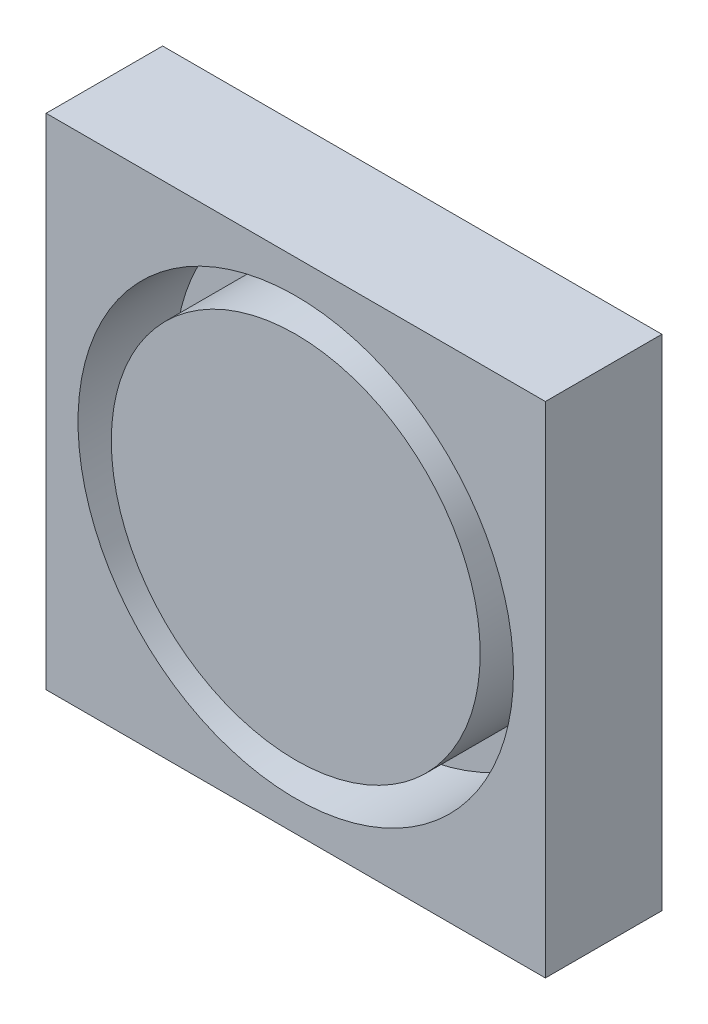
SolidWorks part; units mm, degrees
ref_plane "前视基准面" through (0, 0, 0) normal (0, 0, 1) x (1, 0, 0)
ref_plane "上视基准面" through (0, 0, 0) normal (0, 1, 0) x (1, 0, 0)
ref_plane "右视基准面" through (0, 0, 0) normal (1, 0, 0) x (0, 0, -1)
sketch "草图1" plane through (0, 0, 0) normal (0, 0, 1) x (1, 0, 0)
  line L1 (0, 0) -> (30, 0)
  line L2 (0, 0) -> (0, -30)
  line L3 (0, -30) -> (30, -30)
  line L4 (30, 0) -> (30, -30)
  dimension "D1" = 30
  dimension "D2" = 30
extrude "凸台-拉伸1" add sketch "草图1" along normal blind 7
ref_plane "基准面1" through (15, 0, 0) normal (-1, 0, 0) x (0, 0, 1)
sketch "草图5" plane through (0, 0, 7) normal (0, 0, 1) x (1, 0, 0)
  line L0 (15, 3.85) -> (15, -3.85) construction
  circle A0 centre (15, -15.083) radius 13.083
  circle A1 centre (15, -15.083) radius 11.083
  dimension "D1" = 26.166
  dimension "D2" = 2
  dimension "D3" = 15.083
extrude "切除-拉伸1" cut sketch "草图5" against normal blind 5.8
sketch "草图6" plane through (0, 0, 7) normal (0, 0, 1) x (1, 0, 0)
  line L0 (6.4482, -16.1475) -> (-130.7324, -16.1475) construction
  line L1 (3.3126, -15.6743) -> (4.9912, -15.0634)
  line L3 (3.3126, -16.6206) -> (4.9912, -17.2316)
  line L7 (4.9912, -17.2316) -> (4.9912, -15.0634)
  arc A0 (3.2279, -15.7818) -> (3.2279, -16.5131) centre (6.4482, -16.1475) ccw
  arc A4 (3.3126, -15.6743) -> (3.2279, -15.7818) centre (3.3571, -15.7965) ccw
  arc A6 (3.3126, -16.6206) -> (3.2279, -16.5131) centre (3.3571, -16.4984) cw
  point P1 (-130.0924, -16.1475)
  point P5 (-130.692, -18.1791)
  point P16 (3.2381, -15.7015)
  point P24 (-130.2224, -16.1475)
  dimension "ra" = 0.13
  dimension "D2" = 3.241
  dimension "rr" = 0.13
  dimension "D1" = 1.457
  dimension "PbS" = 0.892
  dimension "angle" = 40
  dimension "ht" = 0.51
  dimension "Pb" = 2.032
